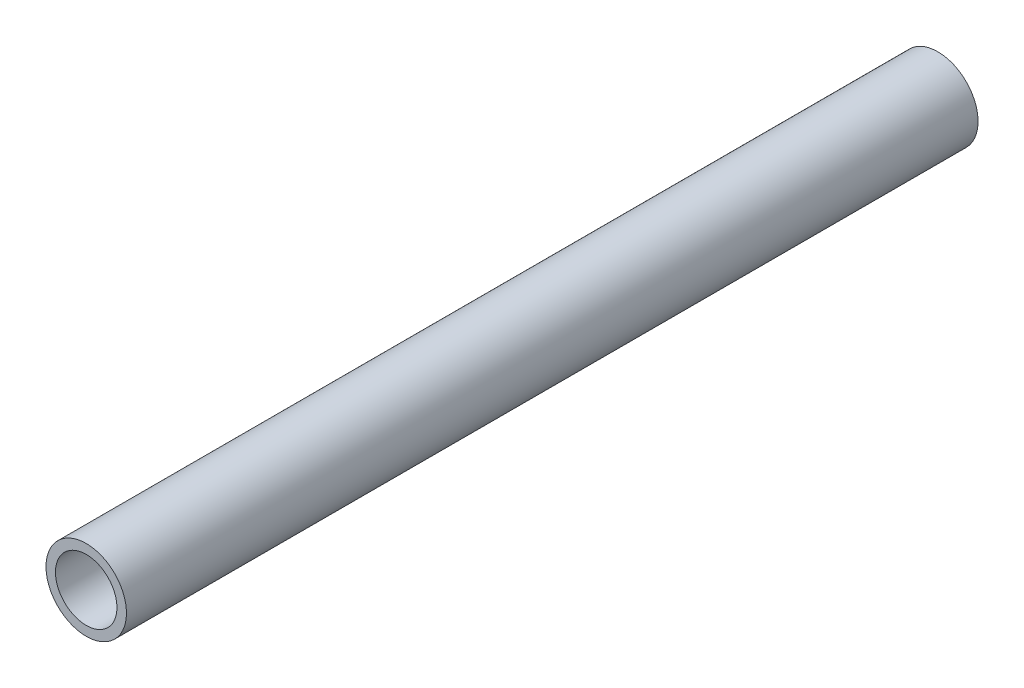
SolidWorks part; units mm, degrees
ref_plane "Piano frontale" through (0, 0, 0) normal (0, 0, 1) x (1, 0, 0)
ref_plane "Piano superiore" through (0, 0, 0) normal (0, 1, 0) x (1, 0, 0)
ref_plane "Piano destro" through (0, 0, 0) normal (1, 0, 0) x (0, 0, -1)
sketch "Schizzo1" plane through (0, 0, 0) normal (0, 0, 1) x (1, 0, 0)
  circle A0 centre (0, 0) radius 3.25
  circle A1 centre (0, 0) radius 4.25
  dimension "D1" = 6.5
  dimension "D2" = 1
extrude "Estrusione-Estrusione1" add sketch "Schizzo1" along normal blind 90
